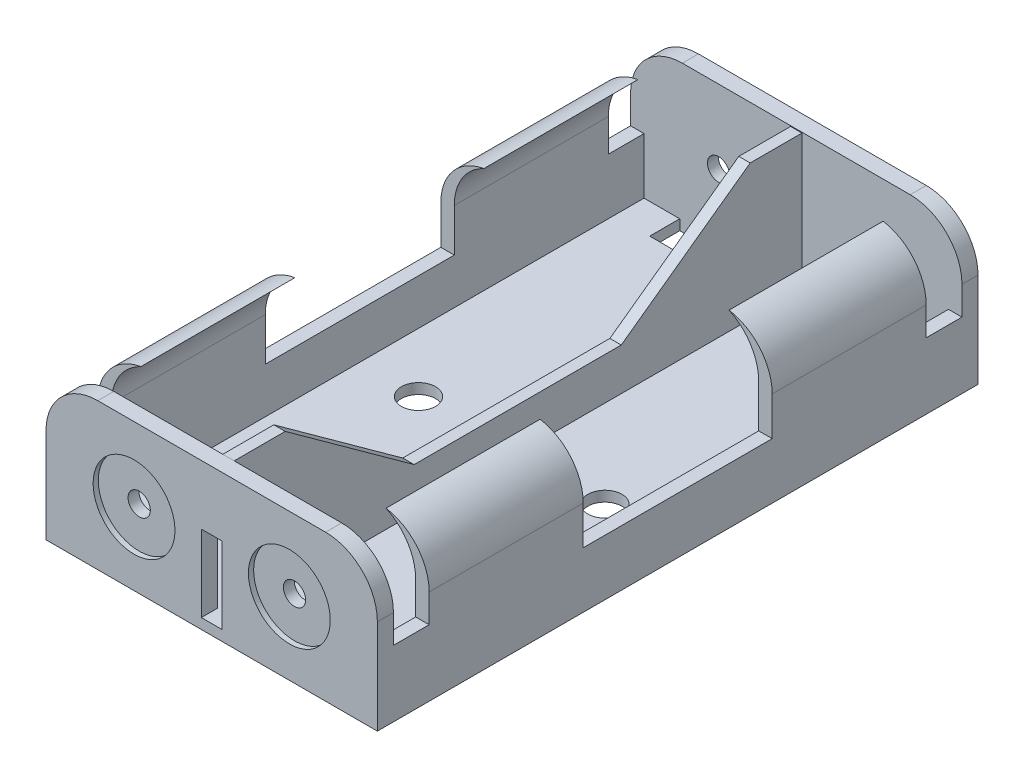
SolidWorks part; units mm, degrees
ref_plane "Front Plane" through (0, 0, 0) normal (0, 0, 1) x (1, 0, 0)
ref_plane "Top Plane" through (0, 0, 0) normal (0, 1, 0) x (1, 0, 0)
ref_plane "Right Plane" through (0, 0, 0) normal (1, 0, 0) x (0, 0, -1)
sketch "Sketch1" plane through (0, 0, 0) normal (0, 0, 1) x (1, 0, 0)
  line L0 (0, 14.14) -> (0, 0) construction
  line L5 (-11, 14.14) -> (11, 14.14)
  line L6 (-16, 9.14) -> (-16, 0)
  line L7 (-16, 0) -> (16, 0)
  line L8 (16, 9.14) -> (16, 0)
  arc A3 (11, 14.14) -> (16, 9.14) centre (11, 9.14) cw
  arc A4 (-11, 14.14) -> (-16, 9.14) centre (-11, 9.14) ccw
  circle A5 centre (-7.5, 7) radius 1.075
  circle A7 centre (7.5, 7) radius 1.075
  point P7 (16, 14.14)
  point P10 (-16, 14.14)
  dimension "D3" = 5
  dimension "D4" = 2.15
  dimension "D5" = 7.5
  dimension "D1" = 32
  dimension "D2" = 14.14
  dimension "D7" = 7
extrude "Boss-Extrude1" add sketch "Sketch1" along normal mid plane 58
sketch "Sketch2" plane through (0, 0, 29) normal (0, 0, 1) x (1, 0, 0)
  line L0 (-16, 0) -> (16, 0) construction
  line L1 (-14.7, 1) -> (14.7, 1)
  line L2 (-14.7, 1) -> (-14.7, 9.55)
  line L3 (-9.7, 14.55) -> (9.7, 14.55)
  line L4 (14.7, 1) -> (14.7, 9.55)
  line L5 (-16, 9.14) -> (-16, 0) construction
  arc A0 (9.7, 14.55) -> (14.7, 9.55) centre (9.7, 9.55) cw
  arc A1 (-14.7, 9.55) -> (-9.7, 14.55) centre (-9.7, 9.55) cw
  point P6 (0, 1)
  point P14 (14.7, 14.55)
  dimension "D4" = 5
  dimension "D1" = 1
  dimension "D2" = 13.55
  dimension "D3" = 1.3
extrude "Cut-Extrude7" cut sketch "Sketch2" against normal offset from surface (54.9 mm away) 1.55 from offset 1.55 up to face at (0, 8.1052, -29) offset against normal yes
sketch "Sketch3" plane through (0, 0, 0) normal (1, 0, 0) x (0, 0, -1)
  line L0 (27.45, 14.069) -> (22.45, 14.069)
  line L1 (22.45, 14.069) -> (10, 5.069)
  line L2 (10, 5.069) -> (-10, 5.069)
  line L3 (-10, 5.069) -> (-22.45, 14.069)
  line L4 (-22.45, 14.069) -> (-27.45, 14.069)
  line L5 (-27.45, 14.069) -> (-27.45, 1)
  line L6 (-27.45, 9.55) -> (-27.45, 1) construction
  line L7 (-27.45, 1) -> (27.45, 1)
  line L8 (27.45, 1) -> (-27.45, 1) construction
  line L9 (27.45, 1) -> (27.45, 9.55) construction
  line L10 (27.45, 1) -> (27.45, 14.069)
  line L11 (27.45, 14.069) -> (27.45, 9.55) construction
  line L12 (-27.45, 14.069) -> (27.45, 14.069) construction
  dimension "D1" = 20
  dimension "D2" = 5
  dimension "D3" = 5
  dimension "D4" = 9
extrude "Boss-Extrude2" add sketch "Sketch3" along normal mid plane 1.1
sketch "Sketch4" plane through (16, 0, 0) normal (1, 0, 0) x (0, 0, -1)
  line L1 (-27.45, 21.4) -> (-24, 21.4)
  line L2 (-27.45, 21.4) -> (-27.45, 6.4)
  line L3 (-27.45, 6.4) -> (-24, 6.4)
  line L4 (-24, 21.4) -> (-24, 6.4)
  line L5 (-9.125, 21.4) -> (9.125, 21.4)
  line L6 (-9.125, 21.4) -> (-9.125, 5.4)
  line L7 (-9.125, 5.4) -> (9.125, 5.4)
  line L8 (9.125, 21.4) -> (9.125, 5.4)
  line L13 (-27.45, 9.55) -> (-27.45, 14.069) construction
  line L14 (-29, 0) -> (29, 0) construction
  line L15 (0, 7.777) -> (0, -7.777) construction
  line L16 (27.45, 6.4) -> (24, 6.4)
  line L17 (24, 21.4) -> (24, 6.4)
  line L18 (27.45, 21.4) -> (24, 21.4)
  line L19 (27.45, 21.4) -> (27.45, 6.4)
  point P12 (0, 5.4)
  dimension "D1" = 3.45
  dimension "D2" = 15
  dimension "D3" = 6.4
  dimension "D4" = 5.4
  dimension "D5" = 18.25
extrude "Cut-Extrude8" cut sketch "Sketch4" against normal up to next
mirror "Mirror1" about plane through (0, 0, 0) normal (1, 0, 0) of "Cut-Extrude8"
sketch "Sketch5" plane through (0, 0, -29) normal (0, 0, -1) x (-1, 0, 0)
  circle A0 centre (-7.5, 7) radius 3.95
  circle A1 centre (7.5, 7) radius 3.95
  dimension "D1" = 7.9
  dimension "D2" = 7.9
extrude "Cut-Extrude9" cut sketch "Sketch5" against normal blind 0.5
mirror "Mirror2" about plane through (0, 0, 0) normal (0, 0, 1) of "Cut-Extrude9"
sketch "Sketch6" plane through (0, 1, 0) normal (0, 1, 0) x (1, 0, 0)
  line L0 (-16, -9.125) -> (-16, 9.125) construction
  line L1 (11, -29) -> (-11, -29) construction
  line L2 (0, -7.777) -> (0, 7.777) construction
  circle A0 centre (-9, -0.03) radius 1.65
  circle A1 centre (9, -0.03) radius 1.65
  dimension "D1" = 3.3
  dimension "D2" = 7
  dimension "D3" = 28.97
extrude "Cut-Extrude10" cut sketch "Sketch6" against normal through all
sketch "Sketch10" plane through (0, 0, 29) normal (0, 0, 1) x (1, 0, 0)
  line L1 (-1, 1) -> (1, 1)
  line L2 (-1, 1) -> (-1, 8.4)
  line L3 (-1, 8.4) -> (1, 8.4)
  line L4 (1, 1) -> (1, 8.4)
  line L5 (-16, 0) -> (16, 0) construction
  point P4 (-1, 0.7719)
  point P7 (0, 8.4)
  dimension "D1" = 2
  dimension "D2" = 7.4
  dimension "D3" = 1
extrude "Cut-Extrude11" cut sketch "Sketch10" against normal up to surface (1.55 mm away) up to face at (0, 7.5978, 27.45)
sketch "Sketch12" plane through (0, 0, -29) normal (0, 0, -1) x (-1, 0, 0)
  line L0 (16, 0) -> (-16, 0) construction
  circle A0 centre (-2.5, 2.5) radius 1.075
  circle A1 centre (2.5, 2.5) radius 1.075
  dimension "D3" = 2.15
  dimension "D1" = 2.5
  dimension "D2" = 2.5
  dimension "D4" = 2.5
extrude "Cut-Extrude12" cut sketch "Sketch12" against normal up to surface (1.55 mm away) up to face at (0, 7.5978, -27.45)
sketch "Sketch14" plane through (0, 0, 0) normal (0, -1, 0) x (1, 0, 0)
  line L1 (-11.25, 27.45) -> (-4.02, 27.45)
  line L2 (-11.25, 27.45) -> (-11.25, 24.55)
  line L3 (-11.25, 24.55) -> (-4.02, 24.55)
  line L4 (-4.02, 27.45) -> (-4.02, 24.55)
  line L5 (-16, 29) -> (-16, -29) construction
  line L6 (3.98, 27.45) -> (11.21, 27.45)
  line L7 (3.98, 27.45) -> (3.98, 24.55)
  line L8 (3.98, 24.55) -> (11.21, 24.55)
  line L9 (11.21, 27.45) -> (11.21, 24.55)
  line L10 (-16, 29) -> (16, 29) construction
  point P12 (0, 0)
  dimension "D1" = 8
  dimension "D2" = 7.23
  dimension "D3" = 7.23
  dimension "D4" = 2.9
  dimension "D5" = 4.75
  dimension "D6" = 2.9
  dimension "D7" = 1.55
  dimension "D8" = 1.55
extrude "Cut-Extrude13" cut sketch "Sketch14" against normal up to surface (1 mm away) up to face at (9, 1, -1.62)
mirror "Mirror3" about plane through (0, 0, 0) normal (0, 0, 1) of "Cut-Extrude13"
